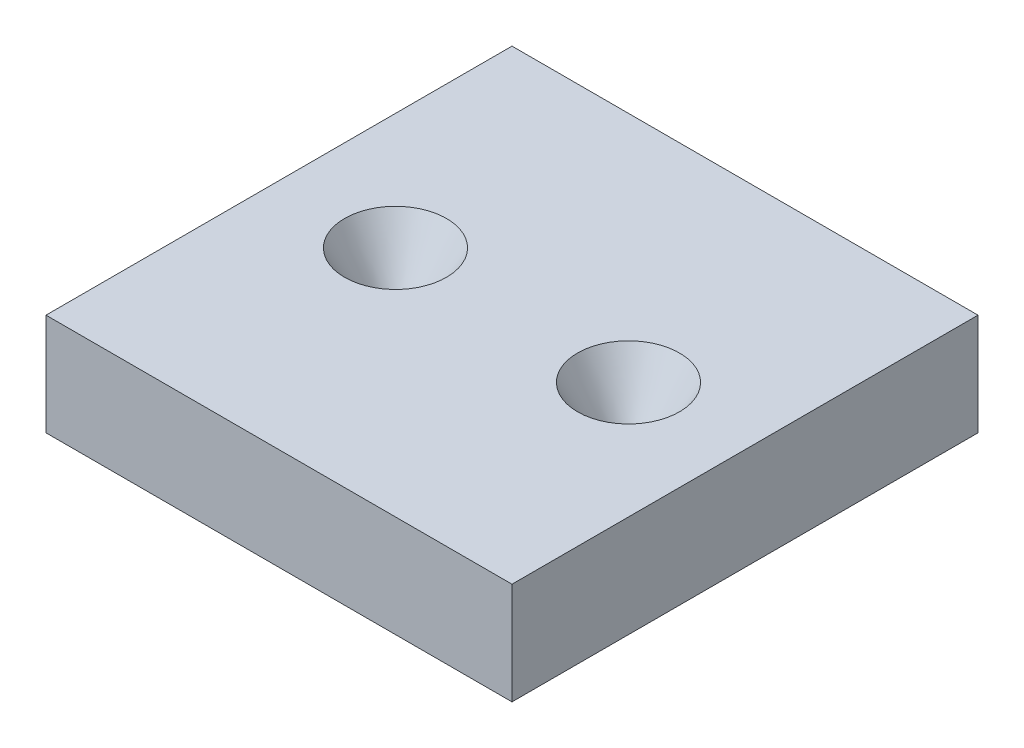
SolidWorks part; units mm, degrees
material "A286 Iron Base Superalloy"
ref_plane "Front Plane" through (0, 0, 0) normal (0, 0, 1) x (1, 0, 0)
ref_plane "Top Plane" through (0, 0, 0) normal (0, 1, 0) x (1, 0, 0)
ref_plane "Right Plane" through (0, 0, 0) normal (1, 0, 0) x (0, 0, -1)
sketch "Sketch1" plane through (0, 0, 0) normal (0, 1, 0) x (1, 0, 0)
  line L1 (16, 16) -> (-16, 16)
  line L2 (16, 16) -> (16, -16)
  line L3 (16, -16) -> (-16, -16)
  line L4 (-16, 16) -> (-16, -16)
  line L5 (16, 16) -> (-16, -16) construction
  line L6 (16, -16) -> (-16, 16) construction
  point P0 (0, 0)
  dimension "D1" = 32
  dimension "D2" = 32
extrude "Boss-Extrude1" add sketch "Sketch1" along normal mid plane 7
sketch "Sketch2" plane through (0, 3.5, 0) normal (0, 1, 0) x (1, 0, 0)
  line L0 (0, 0) -> (-50000, 0) construction
  line L1 (-16, 16) -> (-16, -16) construction
  circle A0 centre (-8, 0) radius 3.5
  circle A1 centre (8, 0) radius 3.5
  dimension "D1" = 7
  dimension "D2" = 7
  dimension "D3" = 16
  dimension "D4" = 8
hole_wizard "CSK for M1.6 Countersunk Flat Head Screw1" positions "3DSketch2" profile "Sketch5" countersink size "M1.6" standard "ISO" end condition through all
sketch3d "3DSketch2"
  point P0 (8, 3.5, 0)
  point P3 (-8, 3.5, 0)
sketch "Sketch5" plane through (8, 3.5, 0) normal (1, 0, 0) x (0, 0, 1)
  line L0 (0, 0) -> (0, 7)
  line L1 (0, 7) -> (0.9, 7)
  line L2 (0.9, 7) -> (0.9, 4.5033)
  line L3 (0.9, 4.5033) -> (3.5, 0)
  line L5 (3.5, 0) -> (0, 0)
  line L6 (-0.9, 4.5033) -> (-3.5, 0) construction
  line L11 (0, -6.35) -> (0, 107.95) construction
  dimension "Thru Hole Dia." = 1.8
  dimension "Thru Hole Depth" = 7
  dimension "Near C'Sink Dia." = 7
  dimension "Near C'Sink Angle" = 60
